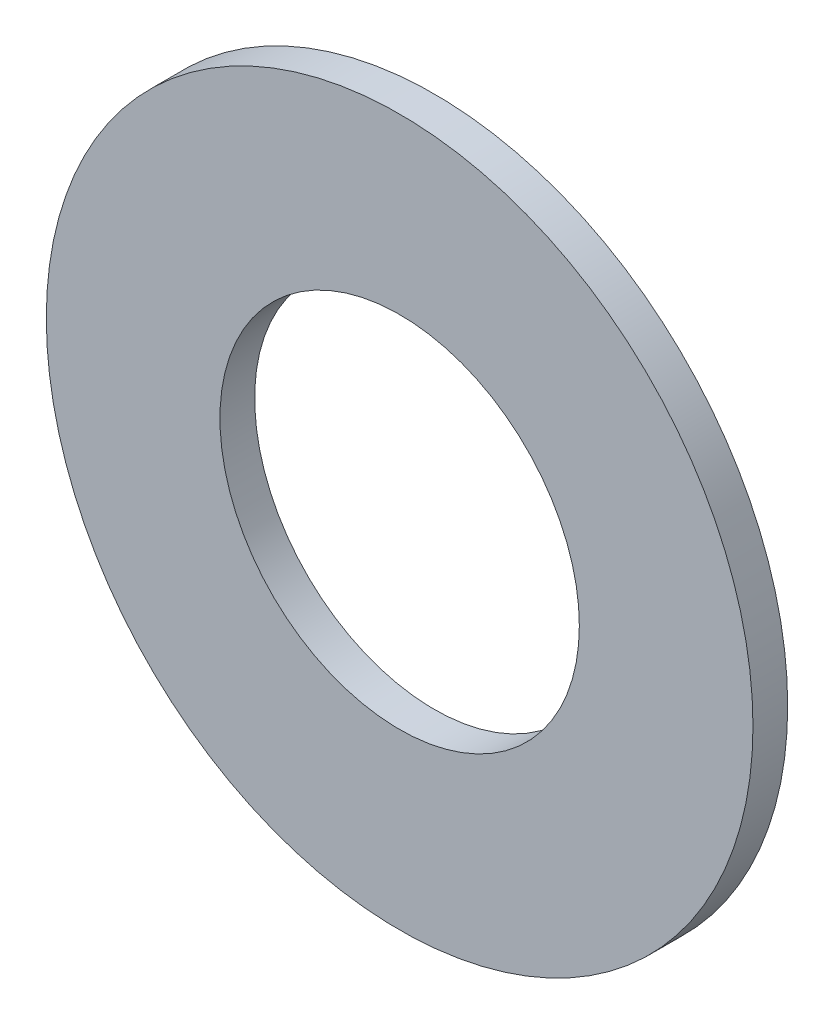
SolidWorks part; units mm, degrees
material "Stainless Steel (ferritic)"
ref_plane "Front Plane" through (0, 0, 0) normal (0, 0, 1) x (1, 0, 0)
ref_plane "Top Plane" through (0, 0, 0) normal (0, 1, 0) x (1, 0, 0)
ref_plane "Right Plane" through (0, 0, 0) normal (1, 0, 0) x (0, 0, -1)
sketch "Sketch1" plane through (0, 0, 0) normal (0, 0, 1) x (1, 0, 0)
  circle A0 centre (0, 0) radius 13.1445
  circle A1 centre (0, 0) radius 25.8445
  dimension "D1" = 26.289
  dimension "D2" = 12.7
extrude "Boss-Extrude2" add sketch "Sketch1" along normal blind 2.54
